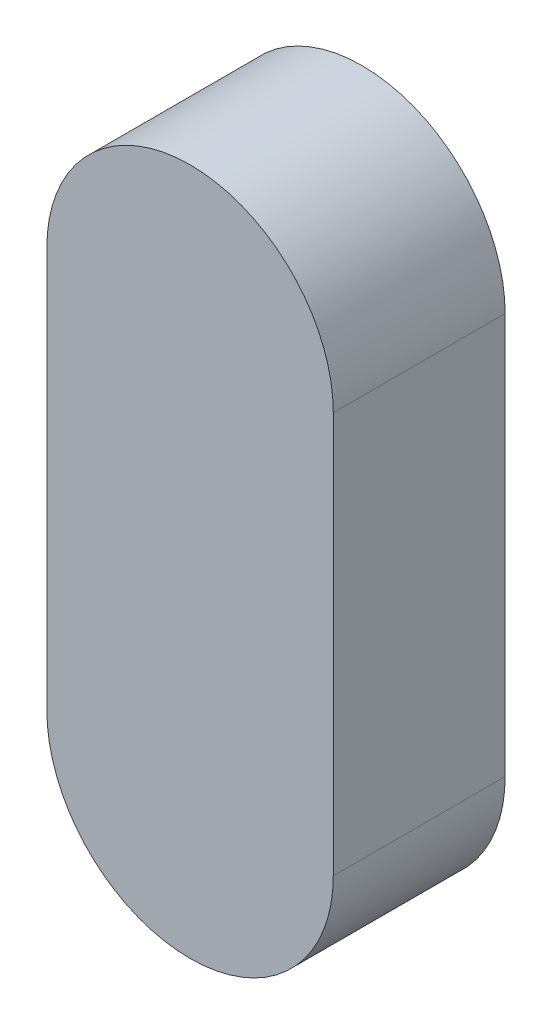
SolidWorks part; units mm, degrees
material "AISI 4130 Steel, annealed at 865C"
ref_plane "Front Plane" through (0, 0, 0) normal (0, 0, 1) x (1, 0, 0)
ref_plane "Top Plane" through (0, 0, 0) normal (0, 1, 0) x (1, 0, 0)
ref_plane "Right Plane" through (0, 0, 0) normal (1, 0, 0) x (0, 0, -1)
sketch "Sketch1" plane through (0, 0, 0) normal (0, 0, 1) x (1, 0, 0)
  line L0 (0, -3.5) -> (0, 3.5) construction
  line L1 (-2.5, -3.5) -> (-2.5, 3.5)
  line L2 (2.5, -3.5) -> (2.5, 3.5)
  arc A0 (-2.5, -3.5) -> (2.5, -3.5) centre (0, -3.5) ccw
  arc A1 (2.5, 3.5) -> (-2.5, 3.5) centre (0, 3.5) ccw
  point P2 (0, 0)
  dimension "D1" = 2.5
  dimension "D2" = 7
extrude "Boss-Extrude1" add sketch "Sketch1" along normal blind 3
